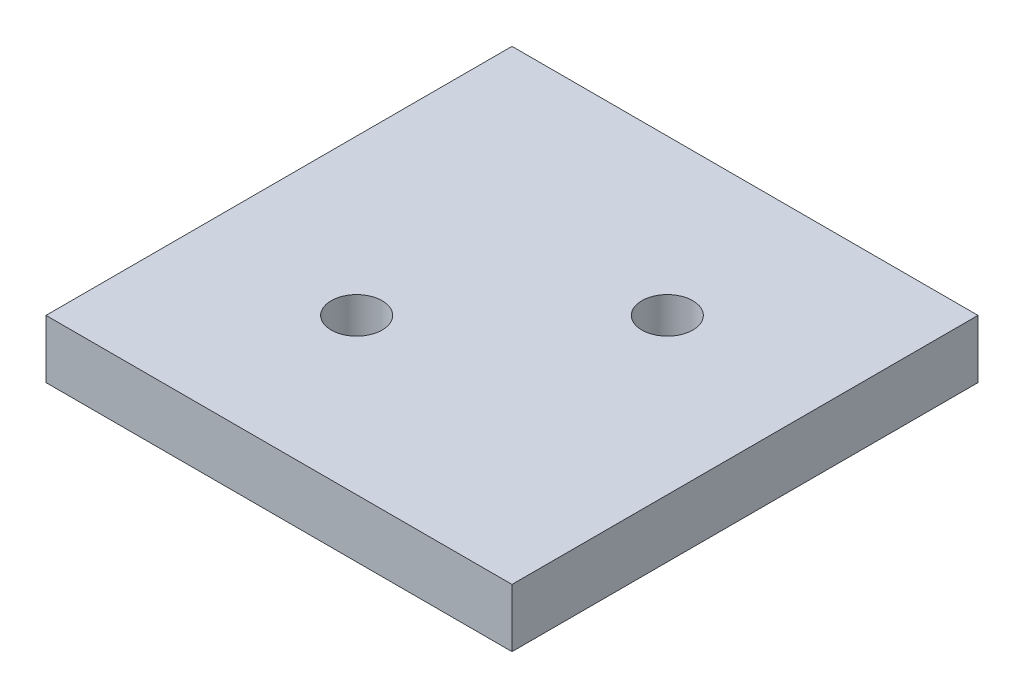
SolidWorks part; units mm, degrees
ref_plane "Front Plane" through (0, 0, 0) normal (0, 0, 1) x (1, 0, 0)
ref_plane "Top Plane" through (0, 0, 0) normal (0, 1, 0) x (1, 0, 0)
ref_plane "Right Plane" through (0, 0, 0) normal (1, 0, 0) x (0, 0, -1)
sketch "Sketch1" plane through (0, 0, 0) normal (0, 1, 0) x (1, 0, 0)
  line L0 (50.8, 50.8) -> (33.8667, 33.8667) construction
  line L1 (0, 0) -> (50.8, 0)
  line L2 (0, 0) -> (0, 50.8)
  line L3 (0, 50.8) -> (50.8, 50.8)
  line L4 (50.8, 0) -> (50.8, 50.8)
  line L5 (33.8667, 33.8667) -> (16.9333, 16.9333) construction
  line L6 (16.9333, 16.9333) -> (0, 0) construction
  circle A0 centre (33.8667, 33.8667) radius 2.7781
  circle A1 centre (16.9333, 16.9333) radius 2.7781
  dimension "D3" = 5.5562
  dimension "D1" = 50.8
  dimension "D2" = 50.8
extrude "Boss-Extrude1" add sketch "Sketch1" against normal blind 6.35
